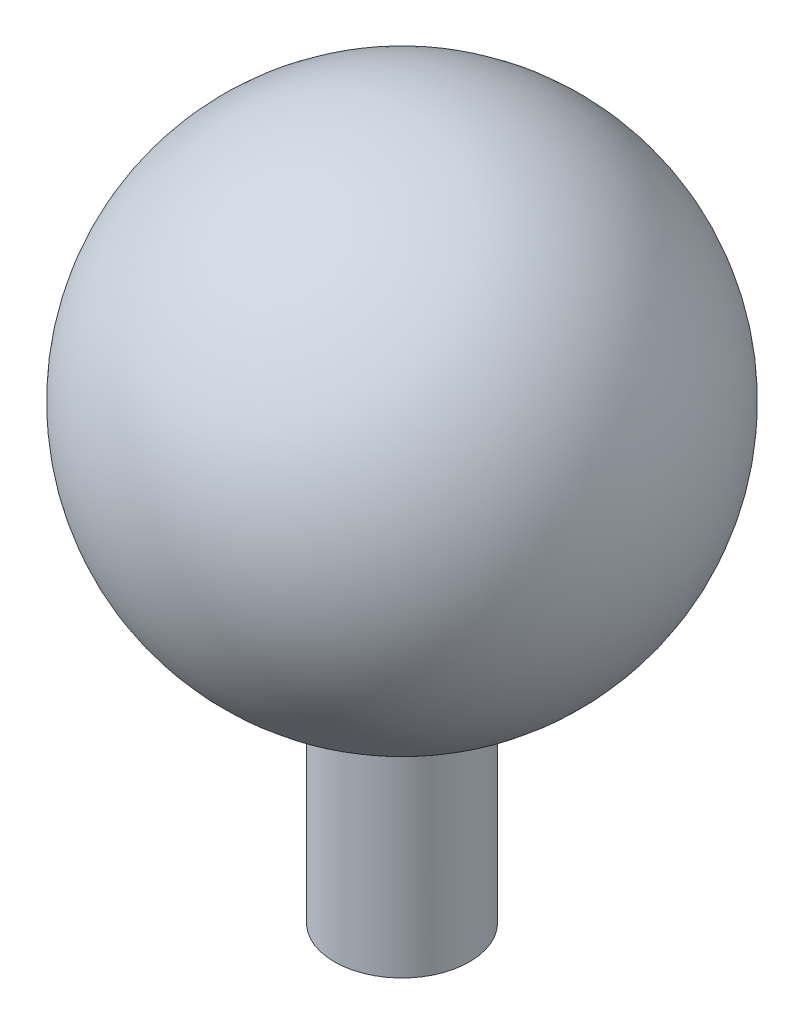
SolidWorks part; units mm, degrees
ref_plane "Front Plane" through (0, 0, 0) normal (0, 0, 1) x (1, 0, 0)
ref_plane "Top Plane" through (0, 0, 0) normal (0, 1, 0) x (1, 0, 0)
ref_plane "Right Plane" through (0, 0, 0) normal (1, 0, 0) x (0, 0, -1)
sketch "Sketch1" plane through (0, 0, 0) normal (0, 0, 1) x (1, 0, 0)
  line L0 (0, 20) -> (0, -20)
  arc A0 (0, -20) -> (0, 20) centre (0, 0) ccw
  dimension "D1" = 40
revolve "Revolve1" add sketch "Sketch1" angle 360 about L0
sketch "Sketch8" plane through (0, 0, 0) normal (0, 0, 1) x (1, 0, 0)
  line L1 (0, 0) -> (5.3766, 0)
  line L2 (0, 0) -> (0, -35.9341)
  line L3 (0, -35.9341) -> (5.3766, -35.9341)
  line L4 (5.3766, 0) -> (5.3766, -35.9341)
revolve "Revolve2" add sketch "Sketch8" angle 360 about L2
